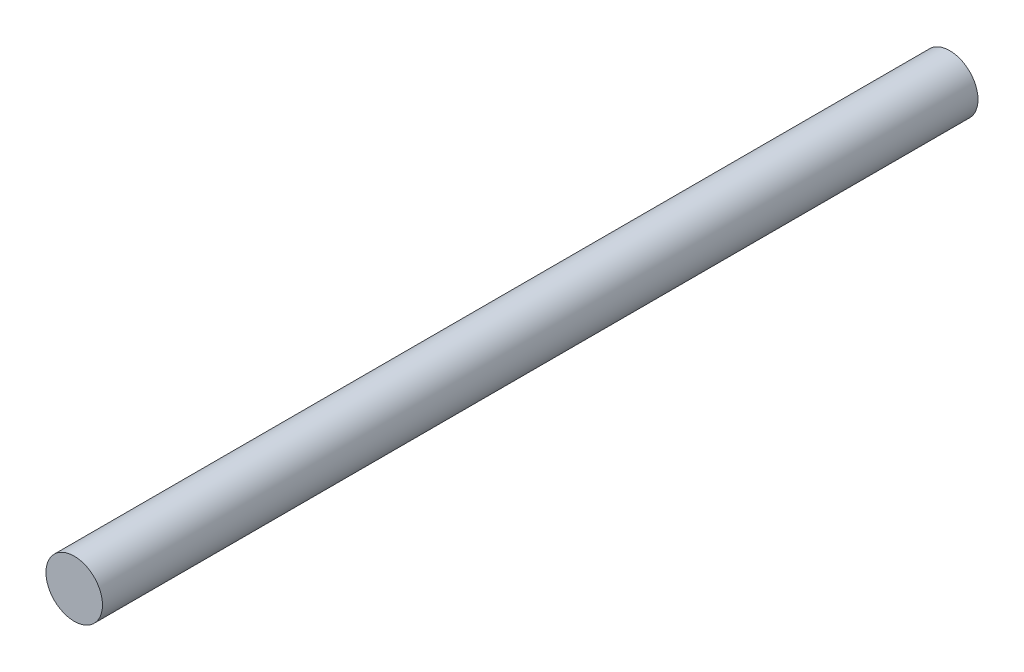
SolidWorks part; units mm, degrees
ref_plane "Front Plane" through (0, 0, 0) normal (0, 0, 1) x (1, 0, 0)
ref_plane "Top Plane" through (0, 0, 0) normal (0, 1, 0) x (1, 0, 0)
ref_plane "Right Plane" through (0, 0, 0) normal (1, 0, 0) x (0, 0, -1)
sketch "Sketch1" plane through (0, 0, 0) normal (0, 0, 1) x (1, 0, 0)
  circle A0 centre (0, 0) radius 0.51
  dimension "D1" = 1.02
extrude "Boss-Extrude1" add sketch "Sketch1" along normal blind 15.8
